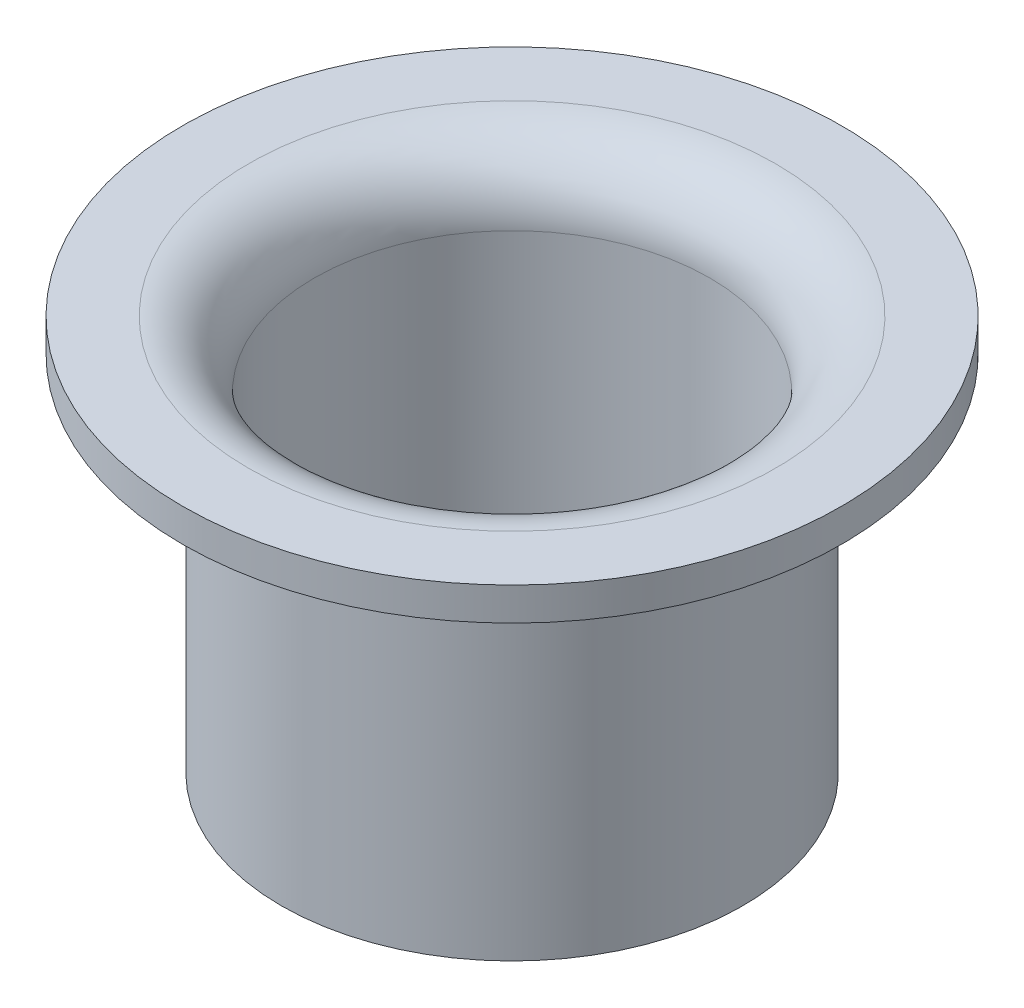
SolidWorks part; units mm, degrees
material "1.2826 GLY"
ref_plane "Ebene1" through (0, 0, 0) normal (0, 0, 1) x (1, 0, 0)
ref_plane "Ebene2" through (0, 0, 0) normal (0, 1, 0) x (1, 0, 0)
ref_plane "Ebene3" through (0, 0, 0) normal (1, 0, 0) x (0, 0, -1)
sketch "Skizze1" plane through (0, 0, 0) normal (0, 0, 1) x (1, 0, 0)
  line L0 (-6, -11) -> (-7, -11)
  line L1 (-7, -11) -> (-7, -1)
  line L2 (-8, 0) -> (-10, 0)
  line L3 (-10, 0) -> (-10, 1)
  line L4 (-10, 1) -> (-8, 1)
  line L5 (0, 7.791) -> (0, -11.8128) construction
  line L6 (-6, -1) -> (-6, -11)
  arc A0 (-8, 0) -> (-7, -1) centre (-8, -1) cw
  arc A1 (-6, -1) -> (-8, 1) centre (-8, -1) ccw
  dimension "D6" = 1
  dimension "D7" = 2
  dimension "D1" = 12
  dimension "D2" = 14
  dimension "D3" = 12
  dimension "D4" = 1
  dimension "D5" = 20
revolve "Basis-Rotation" add sketch "Skizze1" angle 360 about L5
